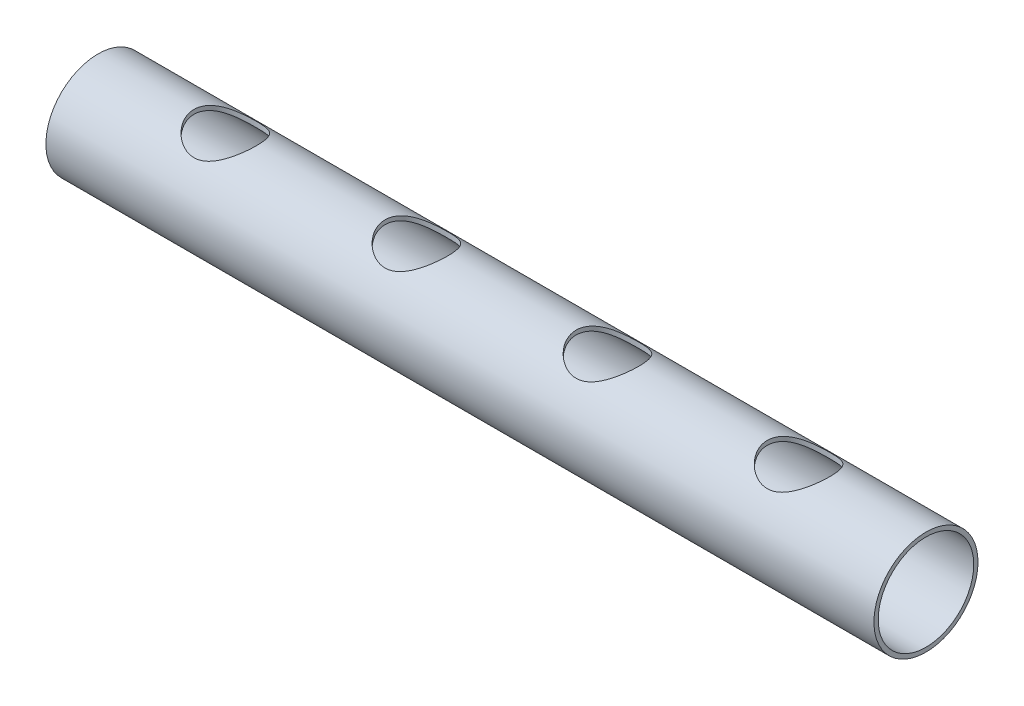
SolidWorks part; units mm, degrees
ref_plane "Front Plane" through (0, 0, 0) normal (0, 0, 1) x (1, 0, 0)
ref_plane "Top Plane" through (0, 0, 0) normal (0, 1, 0) x (1, 0, 0)
ref_plane "Right Plane" through (0, 0, 0) normal (1, 0, 0) x (0, 0, -1)
sketch "Sketch1" plane through (0, 0, 0) normal (1, 0, 0) x (0, 0, -1)
  circle A0 centre (0, 0) radius 38.1
  circle A1 centre (0, 0) radius 41.5
  dimension "D1" = 76.2
  dimension "D2" = 83
extrude "Boss-Extrude1" add sketch "Sketch1" along normal blind 660.4
sketch "Sketch2" plane through (0, 0, 0) normal (0, 1, 0) x (1, 0, 0)
  line L0 (0, 0) -> (660.4, 0) construction
  line L1 (660.4, -41.5) -> (660.4, 41.5) construction
  line L2 (-89.6798, 0) -> (729.4417, 0) construction
  circle A0 centre (101.6, 0) radius 25
  circle A1 centre (254, 0) radius 25
  circle A2 centre (406.4, 0) radius 25
  circle A3 centre (558.8, 0) radius 25
  dimension "D1" = 50
  dimension "D3" = 101.6
  dimension "D2" = 4
extrude "Cut-Extrude1" cut sketch "Sketch2" along normal through all
sketch "Sketch3" plane through (0, 0, 0) normal (0, 0, 1) x (1, 0, 0)
  line L0 (-99.6431, 0) -> (824.8042, 0) construction
